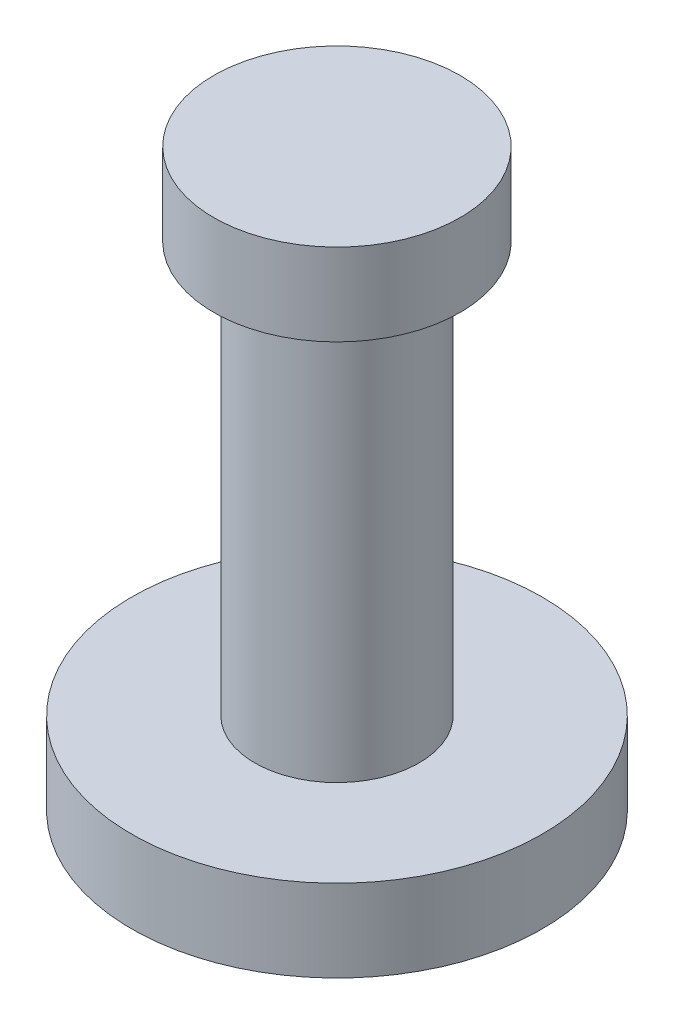
SolidWorks part; units mm, degrees
ref_plane "前视基准面" through (0, 0, 0) normal (0, 0, 1) x (1, 0, 0)
ref_plane "上视基准面" through (0, 0, 0) normal (0, 1, 0) x (1, 0, 0)
ref_plane "右视基准面" through (0, 0, 0) normal (1, 0, 0) x (0, 0, -1)
sketch "草图1" plane through (0, 0, 0) normal (0, 0, 1) x (1, 0, 0)
  line L0 (-42.4215, -10) -> (-17.4215, -10)
  line L9 (-17.4215, -10) -> (-17.4215, 60)
  line L10 (-17.4215, 60) -> (-32.4215, 60)
  line L11 (-32.4215, 60) -> (-32.4215, 50)
  line L12 (-32.4215, 50) -> (-27.4215, 50)
  line L13 (-27.4215, 50) -> (-27.4215, 0)
  line L14 (-27.4215, 0) -> (-42.4215, 0)
  line L15 (-42.4215, 0) -> (-42.4215, -10)
  dimension "D1" = 25
  dimension "D2" = 10
  dimension "D3" = 10
  dimension "D4" = 50
  dimension "D5" = 10
  dimension "D6" = 15
revolve "旋转1" add sketch "草图1" angle 360 about L9
